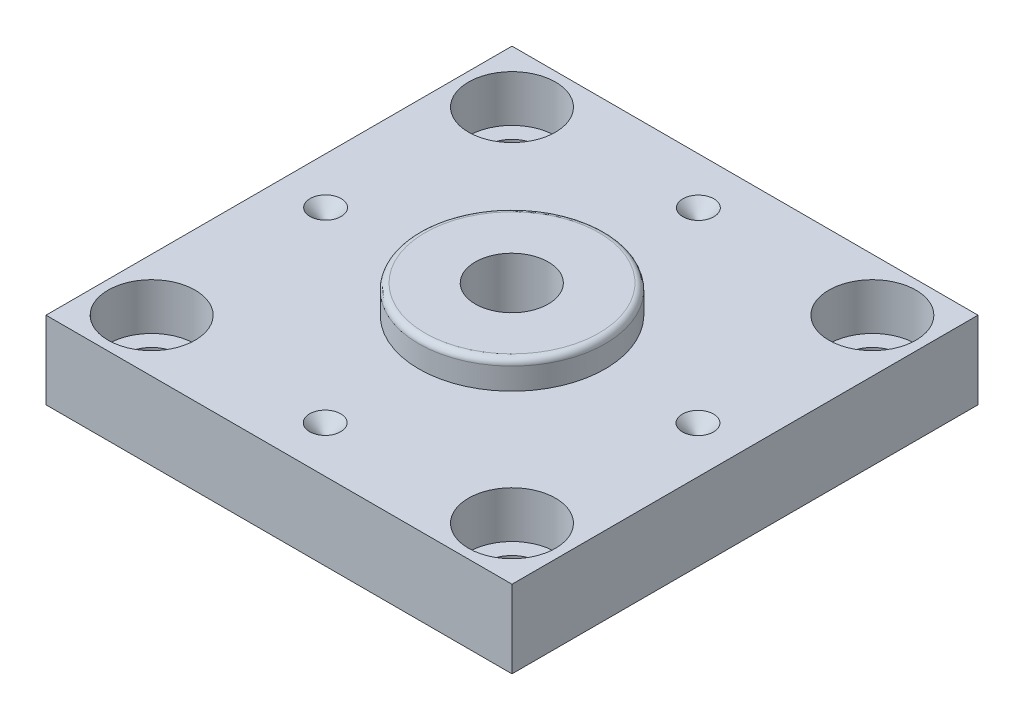
SolidWorks part; units mm, degrees
ref_plane "Ön Düzlem" through (0, 0, 0) normal (0, 0, 1) x (1, 0, 0)
ref_plane "Üst Düzlem" through (0, 0, 0) normal (0, 1, 0) x (1, 0, 0)
ref_plane "Sağ Düzlem" through (0, 0, 0) normal (1, 0, 0) x (0, 0, -1)
sketch "Çizim2" plane through (0, 0, 0) normal (0, 1, 0) x (1, 0, 0)
  line L1 (-75, 75) -> (75, 75)
  line L2 (-75, 75) -> (-75, -75)
  line L3 (-75, -75) -> (75, -75)
  line L4 (75, 75) -> (75, -75)
  line L5 (-75, 75) -> (75, -75) construction
  line L6 (-75, -75) -> (75, 75) construction
  point P0 (0, 0)
extrude "Yükseklik-Ekstrüzyon1" add sketch "Çizim2" along normal blind 25
sketch "Çizim3" plane through (0, 25, 0) normal (0, 1, 0) x (1, 0, 0)
  circle A0 centre (0, 0) radius 30
extrude "Yükseklik-Ekstrüzyon2" add sketch "Çizim3" along normal blind 9
fillet "Radyus1" radius 2 1 edges at (0, 34, 30)
hole_wizard "M25x1.5 Dişli Delik2" positions "3B Çizim1" profile "Çizim6" tap size "M25x1.5" standard "DIN"
sketch3d "3B Çizim1"
  point P0 (0, 0, 0)
  point P3 (-0.0043, 34, 0.0659)
sketch "Çizim6" plane through (-0.0043, 34, 0.0659) normal (1, 0, 0) x (0, 0, 1)
  line L0 (0, 0) -> (0, 34)
  line L1 (0, 34) -> (11.75, 34)
  line L2 (11.75, 34) -> (11.75, 0)
  line L5 (11.75, 0) -> (0, 0)
  line L11 (0, -6.35) -> (0, 107.95) construction
  dimension "Thru Tap Drill Dia." = 23.5
  dimension "Thru Tap Drill Depth" = 34
cosmetic thread "Delik Dişi3" parameters "D2"=25
cosmetic thread "Delik Dişi4" parameters "D2"=25
hole_wizard "Delik1" positions "3B Çizim2" profile "Çizim7" legacy end condition through all
sketch3d "3B Çizim2"
  line L0 (0, 0, 0) -> (0, 0, -38.6113) construction
  line L1 (0, 0, 0) -> (42.5058, 0, 0)
  point P0 (-57.9984, 25, -57.9984)
  point P2 (58.0016, 25, -57.9984)
  point P4 (58.0016, 25, 58.0016)
  point P6 (-57.9984, 25, 58.0016)
  dimension "D1" = 116
  dimension "D2" = 116
  dimension "D3" = 116
  dimension "D4" = 63.16
  dimension "D5" = 63.1571
  dimension "D6" = 63.16
  dimension "D7" = 63.1571
sketch "Çizim7" plane through (-57.9984, 25, -57.9984) normal (1, 0, 0) x (0, 0, 1)
  line L0 (0, 0) -> (0, 25)
  line L1 (0, 25) -> (8.5, 25)
  line L2 (8.5, 25) -> (8.5, 15)
  line L3 (8.5, 15) -> (14, 15)
  line L4 (14, 15) -> (14, 0)
  line L5 (14, 0) -> (0, 0)
  line L6 (0, 110) -> (0, -10) construction
  dimension "Diameter" = 17
  dimension "Depth" = 25
  dimension "C-Bore Diameter" = 28
  dimension "C-Bore Depth" = 15
sketch "Çizim8" plane through (0, 0, 0) normal (0, 0, 1) x (1, 0, 0)
  line L0 (-65, 25) -> (-60, 20)
  line L1 (-75, 25) -> (75, 25) construction
  line L3 (-60, 25) -> (-65, 25)
  line L4 (-60, 20) -> (-60, 25) construction
  line L5 (-60, 20) -> (-60, 25)
  dimension "D1" = 45
  dimension "D2" = 60
  dimension "D3" = 5
revolve "Kes-Döndür1" cut sketch "Çizim8" angle 360 about L4
pattern_circular "Dairesel Kaplama2" count 4 every 90 about axis through (-0.0043, 0, 0.0659) along (0, 1, 0) of "Kes-Döndür1"
